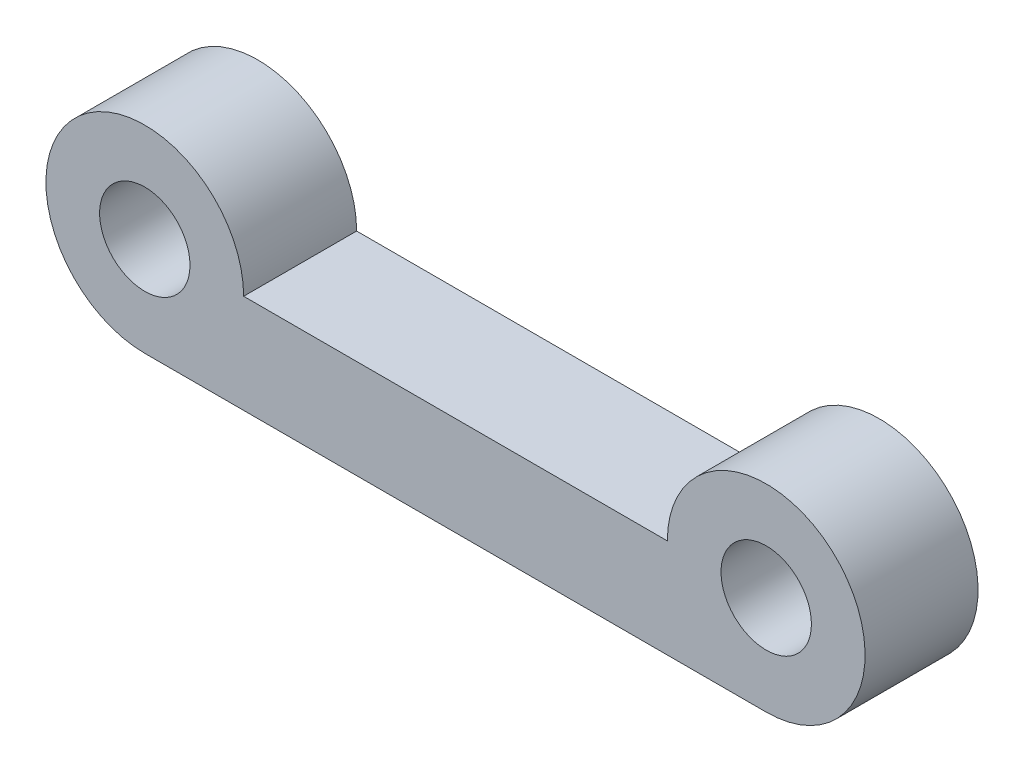
SolidWorks part; units mm, degrees
ref_plane "正面" through (0, 0, 0) normal (0, 0, 1) x (1, 0, 0)
ref_plane "平面" through (0, 0, 0) normal (0, 1, 0) x (1, 0, 0)
ref_plane "右側面" through (0, 0, 0) normal (1, 0, 0) x (0, 0, -1)
sketch "ｽｹｯﾁ1" plane through (0, 0, 0) normal (0, 0, 1) x (1, 0, 0)
  line L0 (0, -3.5) -> (22, -3.5)
  line L1 (3.5, 0) -> (18.5, 0)
  arc A0 (3.5, 0) -> (0, -3.5) centre (0, 0) ccw
  arc A1 (22, -3.5) -> (18.5, 0) centre (22, 0) ccw
  circle A2 centre (0, 0) radius 1.6
  circle A3 centre (22, 0) radius 1.6
  dimension "D3" = 7
  dimension "D4" = 7
  dimension "D2" = 3.2
  dimension "D5" = 3.2
  dimension "D1" = 22
extrude "ﾎﾞｽ - 押し出し1" add sketch "ｽｹｯﾁ1" along normal blind 4
